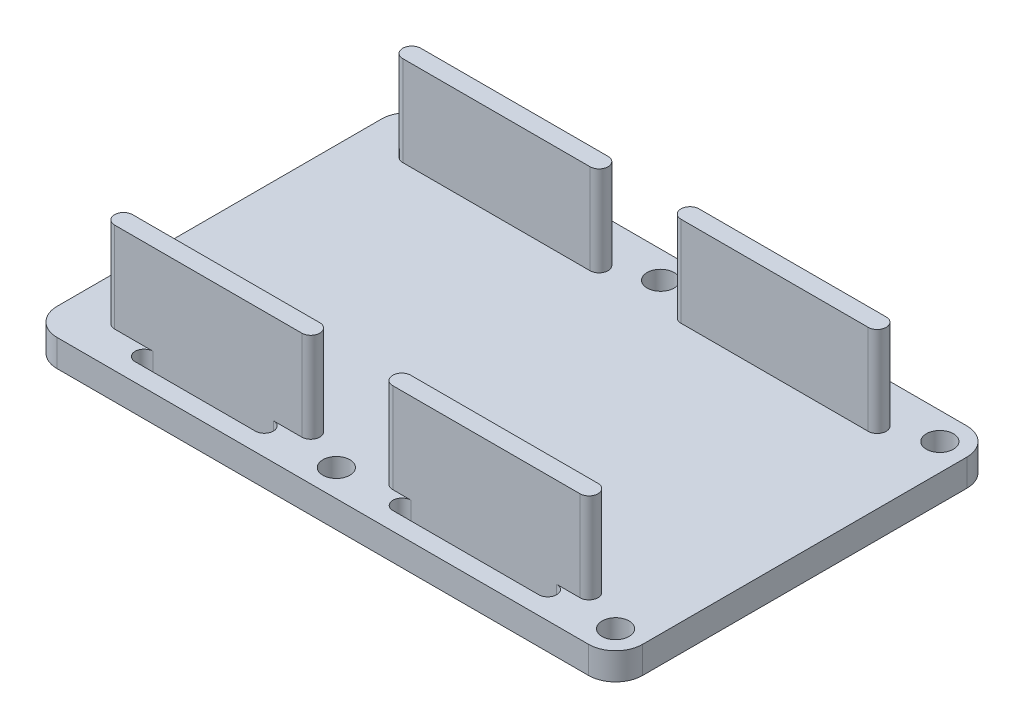
SolidWorks part; units mm, degrees
ref_plane "Front Plane" through (0, 0, 0) normal (0, 0, 1) x (1, 0, 0)
ref_plane "Top Plane" through (0, 0, 0) normal (0, 1, 0) x (1, 0, 0)
ref_plane "Right Plane" through (0, 0, 0) normal (1, 0, 0) x (0, 0, -1)
sketch "Sketch1" plane through (0, 0, 0) normal (0, 1, 0) x (1, 0, 0)
  line L1 (-28, 15) -> (28, 15) construction
  line L2 (-28, 15) -> (-28, -15) construction
  line L3 (-28, -15) -> (28, -15) construction
  line L4 (28, 15) -> (28, -15) construction
  line L5 (-28, 15) -> (28, -15) construction
  line L6 (-28, -15) -> (28, 15) construction
  line L15 (-21.3419, -18) -> (-7.9908, -18)
  line L16 (34, 0) -> (-31, 0) construction
  line L17 (7.2821, -18) -> (23.4653, -18)
  line L19 (7.2821, 18) -> (23.4653, 18)
  line L20 (0, -18) -> (0, 18)
  line L21 (0, -21) -> (31, -21)
  line L22 (34, -18) -> (34, 18)
  line L23 (31, 21) -> (0, 21)
  line L24 (0, 21) -> (-28, 21)
  line L25 (0, -21) -> (-28, -21)
  line L26 (-31, -18) -> (-31, 18)
  line L27 (-21.3419, 18) -> (-7.9908, 18)
  line L28 (-21.3419, 17) -> (-7.9908, 17)
  line L29 (7.2821, 17) -> (23.4653, 17)
  line L30 (-21.3419, -19) -> (-7.9908, -19)
  line L31 (7.2821, -19) -> (23.4653, -19)
  line L32 (-21.3419, 19) -> (-7.9908, 19)
  line L33 (7.2821, 19) -> (23.4653, 19)
  line L34 (-21.3419, -17) -> (-7.9908, -17)
  line L35 (7.2821, -17) -> (23.4653, -17)
  arc A2 (34, 18) -> (31, 21) centre (31, 18) ccw
  arc A3 (31, -21) -> (34, -18) centre (31, -18) ccw
  circle A14 centre (0, 18) radius 1.5
  circle A15 centre (31, 18) radius 1.5
  circle A16 centre (31, -18) radius 1.5
  circle A17 centre (0, -18) radius 1.5
  arc A18 (-28, -21) -> (-31, -18) centre (-28, -18) cw
  arc A19 (-28, 21) -> (-31, 18) centre (-28, 18) ccw
  arc A20 (-21.3419, 17) -> (-21.3419, 19) centre (-21.3419, 18) cw
  arc A21 (-7.9908, 17) -> (-7.9908, 19) centre (-7.9908, 18) ccw
  arc A22 (7.2821, 17) -> (7.2821, 19) centre (7.2821, 18) cw
  arc A23 (23.4653, 17) -> (23.4653, 19) centre (23.4653, 18) ccw
  arc A24 (-21.3419, -19) -> (-21.3419, -17) centre (-21.3419, -18) cw
  arc A25 (-7.9908, -19) -> (-7.9908, -17) centre (-7.9908, -18) ccw
  arc A26 (7.2821, -19) -> (7.2821, -17) centre (7.2821, -18) cw
  arc A27 (23.4653, -19) -> (23.4653, -17) centre (23.4653, -18) ccw
  point P0 (0, 0)
  point P6 (0, 0)
  dimension "D4" = 6
  dimension "D5" = 6
  dimension "D6" = 1
  dimension "D7" = 3
  dimension "D8" = 3
  dimension "D9" = 3
  dimension "D10" = 3
  dimension "D3" = 3
  dimension "D1" = 30
  dimension "D2" = 56
  dimension "D11" = 1
extrude "Boss-Extrude1" add sketch "Sketch1" along normal blind 3
sketch "Sketch2" plane through (0, 3, 0) normal (0, 1, 0) x (1, 0, 0)
  line L0 (-25.6243, 16) -> (-4.8362, 16)
  line L1 (-28, -15) -> (28, -15)
  line L2 (-28, -15) -> (-28, 15)
  line L3 (-28, 15) -> (28, 15)
  line L4 (28, -15) -> (28, 15)
  line L5 (-28, -15) -> (28, 15) construction
  line L6 (-28, 15) -> (28, -15) construction
  line L7 (5.2623, -16) -> (26.0468, -16)
  line L8 (5.2623, 16) -> (26.0468, 16)
  line L9 (-28, 0) -> (28, 0) construction
  line L10 (-25.6243, -16) -> (-4.8362, -16)
  line L11 (-25.6243, 15) -> (-4.8362, 15)
  line L12 (5.2623, 15) -> (26.0468, 15)
  line L13 (-25.6243, -17) -> (-4.8362, -17)
  line L14 (5.2623, -17) -> (26.0468, -17)
  line L15 (-25.6243, 17) -> (-4.8362, 17)
  line L16 (5.2623, 17) -> (26.0468, 17)
  line L17 (-25.6243, -15) -> (-4.8362, -15)
  line L18 (5.2623, -15) -> (26.0468, -15)
  circle A0 centre (0, -18) radius 3
  circle A1 centre (31, -18) radius 3
  circle A2 centre (31, 18) radius 3
  circle A4 centre (0, 18) radius 3
  arc A5 (-25.6243, 15) -> (-25.6243, 17) centre (-25.6243, 16) cw
  arc A6 (-4.8362, 15) -> (-4.8362, 17) centre (-4.8362, 16) ccw
  arc A7 (5.2623, 15) -> (5.2623, 17) centre (5.2623, 16) cw
  arc A8 (26.0468, 15) -> (26.0468, 17) centre (26.0468, 16) ccw
  arc A9 (-25.6243, -17) -> (-25.6243, -15) centre (-25.6243, -16) cw
  arc A10 (-4.8362, -17) -> (-4.8362, -15) centre (-4.8362, -16) ccw
  arc A11 (5.2623, -17) -> (5.2623, -15) centre (5.2623, -16) cw
  arc A12 (26.0468, -17) -> (26.0468, -15) centre (26.0468, -16) ccw
  point P0 (0, 0)
  point P44 (5.2623, 16)
  point P45 (-25.6243, 16)
  dimension "D1" = 56
  dimension "D2" = 30
  dimension "D3" = 1
  dimension "D4" = 1
extrude "Boss-Extrude2" add sketch "Sketch2" along normal blind 10
